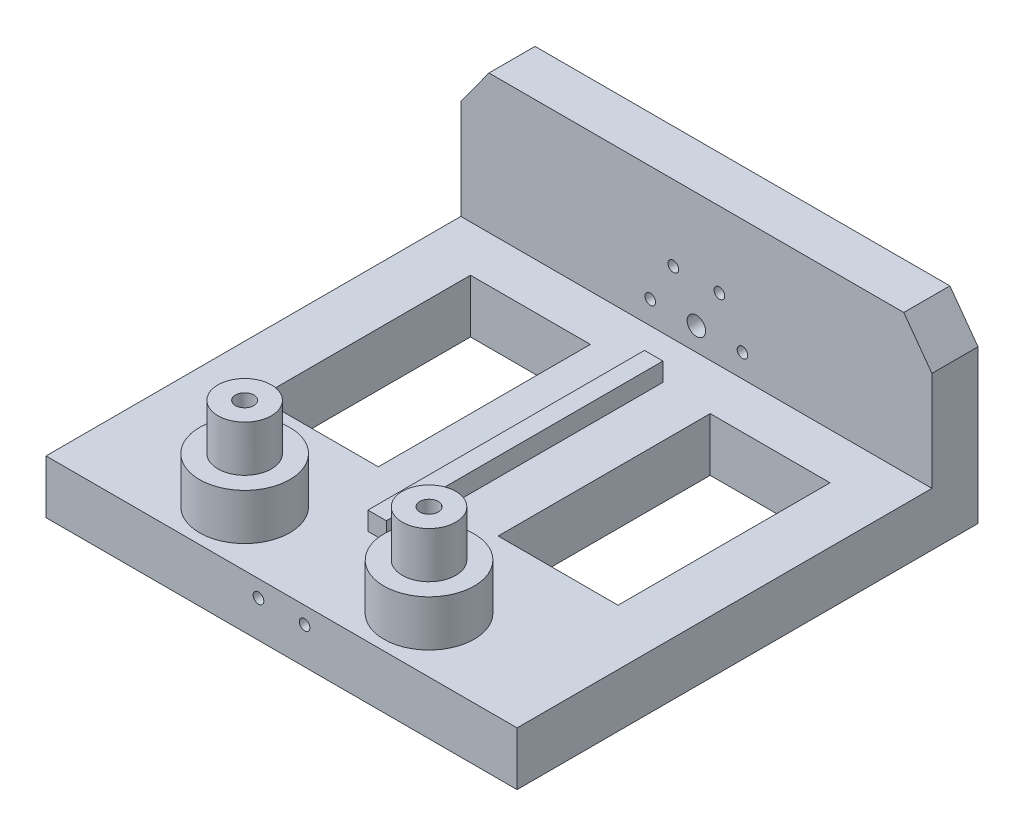
SolidWorks part; units mm, degrees
ref_plane "Front Plane" through (0, 0, 0) normal (0, 0, 1) x (1, 0, 0)
ref_plane "Top Plane" through (0, 0, 0) normal (0, 1, 0) x (1, 0, 0)
ref_plane "Right Plane" through (0, 0, 0) normal (1, 0, 0) x (0, 0, -1)
sketch "Sketch1" plane through (0, 0, 0) normal (0, 0, 1) x (1, 0, 0)
  line L0 (-22.5, 12.5) -> (22.5, 12.5)
  line L2 (-22.5, 12.5) -> (-25.5502, 8.3018)
  line L3 (-25.5502, 8.3018) -> (-25.5502, -8.3018)
  line L4 (-25.5502, -8.3018) -> (-22.5, -12.5)
  line L7 (22.5, -12.5) -> (25.5502, -8.3018)
  line L8 (25.5502, -8.3018) -> (25.5502, 8.3018)
  line L9 (25.5502, 8.3018) -> (22.5, 12.5)
  line L11 (22.5, -12.5) -> (-22.5, -12.5)
  line L12 (-4.314, 0) -> (5.3291, 0) construction
  line L14 (13.6864, 31.312) -> (3.6433, 28.0489) [skipped]
  line L15 (29.4773, 17.2873) -> (19.4342, 20.5505) [skipped]
  line L16 (-7.8954, -24.2997) -> (2.1476, -27.5629) [skipped]
  line L17 (7.8954, -24.2997) -> (17.9385, -21.0365) [skipped]
  arc A0 (-30, 12.5) -> (-30, -12.5) centre (0, 0) ccw construction
  arc A1 (30, -12.5) -> (30, 12.5) centre (0, 0) ccw construction
  circle A2 centre (0, 0) radius 1
  circle A3 centre (0, 0) radius 5 construction
  circle A4 centre (-5, 0) radius 0.575
  circle A5 centre (-2.5, 4.3301) radius 0.575
  circle A6 centre (2.5, 4.3301) radius 0.575
  circle A7 centre (5, 0) radius 0.575
  circle A8 centre (2.5, -4.3301) radius 0.575
  circle A9 centre (-2.5, -4.3301) radius 0.575
  point P41 (0, 0)
  dimension "D1" = 65
  dimension "D4" = 10
  dimension "D5" = 1.15
  dimension "D6" = 2
  dimension "D2" = 45
  dimension "D3" = 25
extrude "Boss-Extrude1" add sketch "Sketch1" along normal blind 5
sketch "Sketch2" plane through (0, 0, 5) normal (0, 0, 1) x (1, 0, 0)
  line L0 (-25.5502, 8.3018) -> (25.5502, 8.3018)
  line L1 (-25.5502, -2.5) -> (25.5502, -2.5)
  line L8 (-22.5, 12.5) -> (-25.5502, 8.3018)
  line L9 (-25.5502, 8.3018) -> (-25.5502, -8.3018)
  line L10 (-25.5502, -8.3018) -> (-22.5, -12.5)
  line L11 (-25.5502, -8.3018) -> (-22.5, -12.5)
  line L13 (25.5502, -8.3018) -> (25.5502, 8.3018)
  line L14 (25.5502, 8.3018) -> (22.5, 12.5)
  line L15 (22.5, 12.5) -> (-22.5, 12.5)
  line L16 (-22.5, 12.5) -> (-25.5502, 8.3018)
  line L17 (-25.5502, 8.3018) -> (-25.5502, -8.3018)
  line L21 (25.5502, -8.3018) -> (25.5502, 8.3018)
  line L22 (25.5502, 8.3018) -> (22.5, 12.5)
  line L23 (22.5, 12.5) -> (-22.5, 12.5)
  line L25 (-22.5, -12.5) -> (22.5, -12.5)
  line L26 (-22.5, -12.5) -> (22.5, -12.5)
  line L27 (22.5, -12.5) -> (25.5502, -8.3018)
  line L28 (22.5, -12.5) -> (25.5502, -8.3018)
  dimension "D1" = 0
extrude "Boss-Extrude2" add sketch "Sketch2" along normal blind 45
sketch "Sketch4" plane through (0, -2.5, 0) normal (0, 1, 0) x (1, 0, 0)
  line L1 (1, -9.6289) -> (-1, -9.6289)
  line L2 (1, -9.6289) -> (1, -39.6289)
  line L3 (1, -39.6289) -> (-1, -39.6289)
  line L4 (-1, -9.6289) -> (-1, -39.6289)
  line L5 (1, -9.6289) -> (-1, -39.6289) construction
  line L6 (1, -39.6289) -> (-1, -9.6289) construction
  point P0 (0, -24.6289)
  dimension "D1" = 30
  dimension "D2" = 2
extrude "Boss-Extrude3" add sketch "Sketch4" along normal blind 2
sketch "Sketch5" plane through (0, -2.5, 0) normal (0, 1, 0) x (1, 0, 0)
  line L0 (13, -21.5) -> (13, -22.0245) construction
  line L1 (19.5, -33) -> (6.5, -33)
  line L2 (19.5, -33) -> (19.5, -10)
  line L3 (19.5, -10) -> (6.5, -10)
  line L4 (6.5, -33) -> (6.5, -10)
  line L5 (19.5, -33) -> (6.5, -10) construction
  line L6 (19.5, -10) -> (6.5, -33) construction
  line L7 (0, 14.9773) -> (0, -52.3516) construction
  line L8 (-19.5, -10) -> (-6.5, -10)
  line L9 (13, -21.5) -> (22.2026, -21.5) construction
  line L10 (-6.5, -33) -> (-6.5, -10)
  line L11 (-19.5, -33) -> (-6.5, -33)
  line L12 (-25.5502, -5) -> (25.5502, -5) construction
  line L13 (1, -39.6289) -> (1, -9.6289) construction
  line L14 (-19.5, -33) -> (-19.5, -10)
  point P0 (13, -21.5)
  point P5 (13, -21.7622)
  point P20 (13, -28)
  point P23 (-13, -28)
  dimension "D1" = 5
  dimension "25" = 23
  dimension "D2" = 13
  dimension "D3" = 28
  dimension "D4" = 12
extrude "Cut-Extrude1" cut sketch "Sketch5" against normal blind 16
sketch "Sketch6" plane through (0, -2.5, 0) normal (0, 1, 0) x (1, 0, 0)
  line L0 (13, -33.5) -> (13, -10.1883) construction
  line L2 (-30.8988, -22) -> (25.4791, -22) construction
  line L3 (0, 9.5569) -> (0, -17.5574) construction
  line L4 (-13, -33.5) -> (-13, -10.1883) construction
  line L10 (19.5, -33) -> (19.5, -10) construction
  line L11 (6.5, -10) -> (6.5, -33) construction
  line L12 (19.5, -10) -> (6.5, -10) construction
  circle A1 centre (10, -44) radius 2.9
  circle A3 centre (-10, -44) radius 2.9
  dimension "D2" = 22
  dimension "D5" = 5.8
  dimension "D1" = 12
  dimension "D3" = 20
extrude "Boss-Extrude4" add sketch "Sketch6" along normal blind 10
sketch "Sketch7" plane through (0, 7.5, 0) normal (0, 1, 0) x (1, 0, 0)
  circle A1 centre (10, -44) radius 1
  circle A2 centre (-10, -44) radius 1
  dimension "D2" = 2
  dimension "D3" = 2
extrude "Cut-Extrude2" cut sketch "Sketch7" against normal through all both and the other way through all
sketch "Sketch11" plane through (0, -2.5, 0) normal (0, 1, 0) x (1, 0, 0)
  circle A2 centre (10, -44) radius 2.9 construction
  circle A3 centre (10, -44) radius 2.9
  circle A4 centre (-10, -44) radius 2.9 construction
  circle A5 centre (-10, -44) radius 2.9
  circle A7 centre (-10, -44) radius 4.9
  circle A8 centre (10, -44) radius 4.9
  dimension "D1" = 2
extrude "Boss-Extrude5" add sketch "Sketch11" along normal blind 5
sketch "Sketch13" plane through (-25.5502, 0, 0) normal (-1, 0, 0) x (0, 0, 1)
  line L0 (0, -8.3018) -> (-5.2349, -12.2481)
  line L1 (-5.2349, -12.2481) -> (12.3003, -20.5374)
  line L2 (12.3003, -20.5374) -> (51.1434, -17.8275)
  line L3 (51.1434, -17.8275) -> (57.1479, -8.3018)
  line L4 (57.1479, -8.3018) -> (50, -8.3018)
  line L6 (0, 8.3018) -> (0, -8.3018)
  line L7 (0, -8.3018) -> (50, -8.3018)
  line L8 (50, -8.3018) -> (50, -2.5)
  line L9 (50, -2.5) -> (5, -2.5)
  line L10 (5, -2.5) -> (5, 8.3018)
  line L11 (5, 8.3018) -> (0, 8.3018)
  line L13 (0, -8.3018) -> (50, -8.3018)
  dimension "D1" = 0
extrude "Cut-Extrude4" cut sketch "Sketch13" against normal through all both and the other way through all
